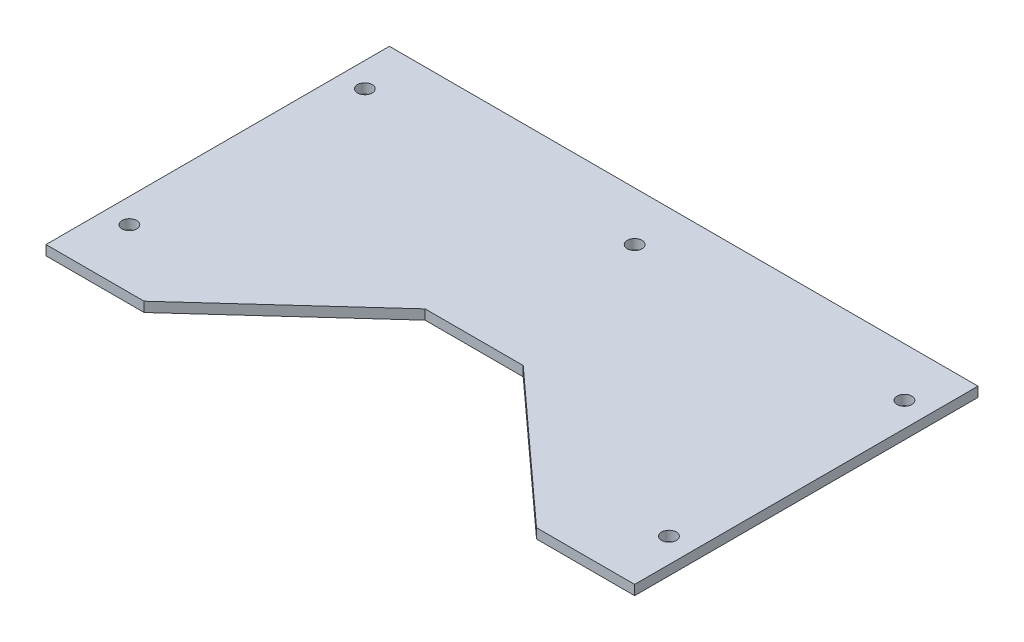
SolidWorks part; units mm, degrees
material "6061-T6 (SS)"
ref_plane "Front Plane" through (0, 0, 0) normal (0, 0, 1) x (1, 0, 0)
ref_plane "Top Plane" through (0, 0, 0) normal (0, 1, 0) x (1, 0, 0)
ref_plane "Right Plane" through (0, 0, 0) normal (1, 0, 0) x (0, 0, -1)
sketch "Sketch1" plane through (0, 0, 0) normal (0, 1, 0) x (1, 0, 0)
  line L0 (-76.2, 39.7899) -> (76.2, 39.7899)
  line L1 (76.2, 39.7899) -> (76.2, -49.1101)
  line L2 (76.2, -49.1101) -> (50.8, -49.1101)
  line L3 (50.8, -49.1101) -> (12.7, -14.4582)
  line L4 (12.7, -14.4582) -> (-12.7, -14.4582)
  line L5 (-12.7, -14.4582) -> (-50.8, -49.1101)
  line L6 (-50.8, -49.1101) -> (-76.2, -49.1101)
  line L7 (-76.2, -49.1101) -> (-76.2, 39.7899)
  circle A0 centre (69.85, 27.0899) radius 1.905
  circle A1 centre (0, 27.0899) radius 1.905
  circle A2 centre (-69.85, 27.0899) radius 1.905
  circle A3 centre (69.85, -33.8701) radius 1.905
  circle A4 centre (-69.85, -33.8701) radius 1.905
  point P2 (0, 39.7899)
  point P10 (0, -14.4582)
  dimension "D9" = 3.81
  dimension "D11" = 3.81
  dimension "D1" = 88.9
  dimension "D2" = 152.4
  dimension "D3" = 88.9
  dimension "D4" = 25.4
  dimension "D5" = 25.4
  dimension "D6" = 25.4
  dimension "D7" = 12.7
  dimension "D8" = 6.35
  dimension "D12" = 60.96
  dimension "D10" = 3
  dimension "D13" = 2
extrude "Boss-Extrude1" add sketch "Sketch1" along normal mid plane 2.54
